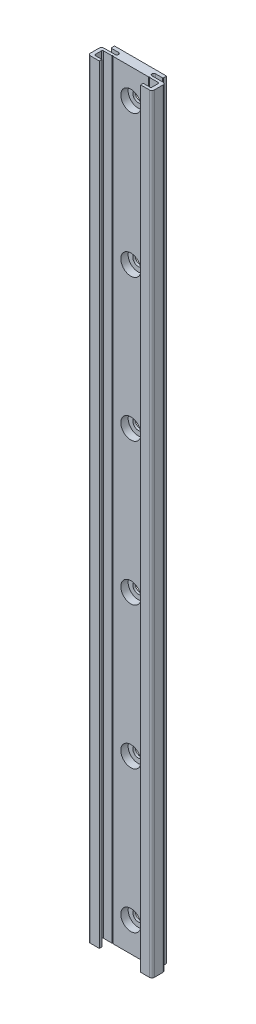
SolidWorks part; units mm, degrees
ref_plane "Front" through (0, 0, 0) normal (0, 0, 1) x (1, 0, 0)
ref_plane "Top" through (0, 0, 0) normal (0, 1, 0) x (1, 0, 0)
ref_plane "Right" through (0, 0, 0) normal (1, 0, 0) x (0, 0, -1)
ref_plane "Plane1" through (0, 30, 0) normal (0, -1, 0) x (1, 0, 0)
sketch "Sketch1" plane through (0, 30, 0) normal (0, -1, 0) x (1, 0, 0)
  line L0 (-7.8, 1.5) -> (-10.8, 1.5)
  line L1 (-11, 1.3) -> (-11, 0)
  line L2 (-11, 0) -> (11, 0)
  line L3 (11, 0) -> (11, 1.3)
  line L4 (10.8, 1.5) -> (7.8, 1.5)
  line L5 (7.8, 3) -> (12.5, 3)
  line L6 (13.5, 4) -> (13.5, 7.7)
  line L7 (12.5, 8.7) -> (8.75, 8.7)
  line L8 (8.75, 8.7) -> (8.75, 7.6)
  line L9 (8.75, 7.6) -> (11.5, 7.6)
  line L10 (12, 7.1) -> (12, 4.6)
  line L11 (11.5, 4.1) -> (7.95, 4.1)
  line L12 (7.55, 4.1) -> (-7.55, 4.1)
  line L13 (-7.95, 4.1) -> (-11.5, 4.1)
  line L14 (-12, 4.6) -> (-12, 7.1)
  line L15 (-11.5, 7.6) -> (-8.75, 7.6)
  line L16 (-8.75, 7.6) -> (-8.75, 8.7)
  line L17 (-8.75, 8.7) -> (-12.5, 8.7)
  line L18 (-13.5, 7.7) -> (-13.5, 4)
  line L19 (-12.5, 3) -> (-7.8, 3)
  arc A0 (-7.8, 3) -> (-7.8, 1.5) centre (-7.8, 2.25) cw
  arc A1 (-10.8, 1.5) -> (-11, 1.3) centre (-10.8, 1.3) ccw
  arc A2 (11, 1.3) -> (10.8, 1.5) centre (10.8, 1.3) ccw
  arc A3 (7.8, 1.5) -> (7.8, 3) centre (7.8, 2.25) cw
  arc A4 (12.5, 3) -> (13.5, 4) centre (12.5, 4) ccw
  arc A5 (13.5, 7.7) -> (12.5, 8.7) centre (12.5, 7.7) ccw
  arc A6 (11.5, 7.6) -> (12, 7.1) centre (11.5, 7.1) cw
  arc A7 (12, 4.6) -> (11.5, 4.1) centre (11.5, 4.6) cw
  arc A8 (7.95, 4.1) -> (7.55, 4.1) centre (7.75, 4.1) cw
  arc A9 (-7.55, 4.1) -> (-7.95, 4.1) centre (-7.75, 4.1) cw
  arc A10 (-11.5, 4.1) -> (-12, 4.6) centre (-11.5, 4.6) cw
  arc A11 (-12, 7.1) -> (-11.5, 7.6) centre (-11.5, 7.1) cw
  arc A12 (-12.5, 8.7) -> (-13.5, 7.7) centre (-12.5, 7.7) ccw
  arc A13 (-13.5, 4) -> (-12.5, 3) centre (-12.5, 4) ccw
extrude "Boss-Extrude1" add sketch "Sketch1" against normal blind 325
hole_wizard "CBORE for M4 Hex Head Machine Screw1" positions "Sketch3" profile "Sketch2" counterbore size "M4" standard "ANSI Metric"
sketch "Sketch3" plane through (0, 0, 4.1) normal (0, 0, 1) x (1, 0, 0)
  point P0 (0, 42.5)
sketch "Sketch2" plane through (0, 42.5, 4.1) normal (1, 0, 0) x (0, -1, 0)
  line L0 (0, 0) -> (0, 4.1)
  line L1 (0, 4.1) -> (2.25, 4.1)
  line L3 (2.25, 4.1) -> (2.25, 3.1)
  line L4 (2.25, 3.1) -> (4.25, 3.1)
  line L5 (4.25, 3.1) -> (4.25, 0)
  line L7 (4.25, 0) -> (0, 0)
  line L11 (0, -6.35) -> (0, 107.95) construction
  dimension "Thru Hole Dia." = 4.5
  dimension "Thru Hole Depth" = 4.1
  dimension "C'Bore Dia." = 8.5
  dimension "C'Bore Depth" = 3.1
pattern_linear "LPattern1" count 6 spacing 60 along (0, 1, 0) of "CBORE for M4 Hex Head Machine Screw1"
